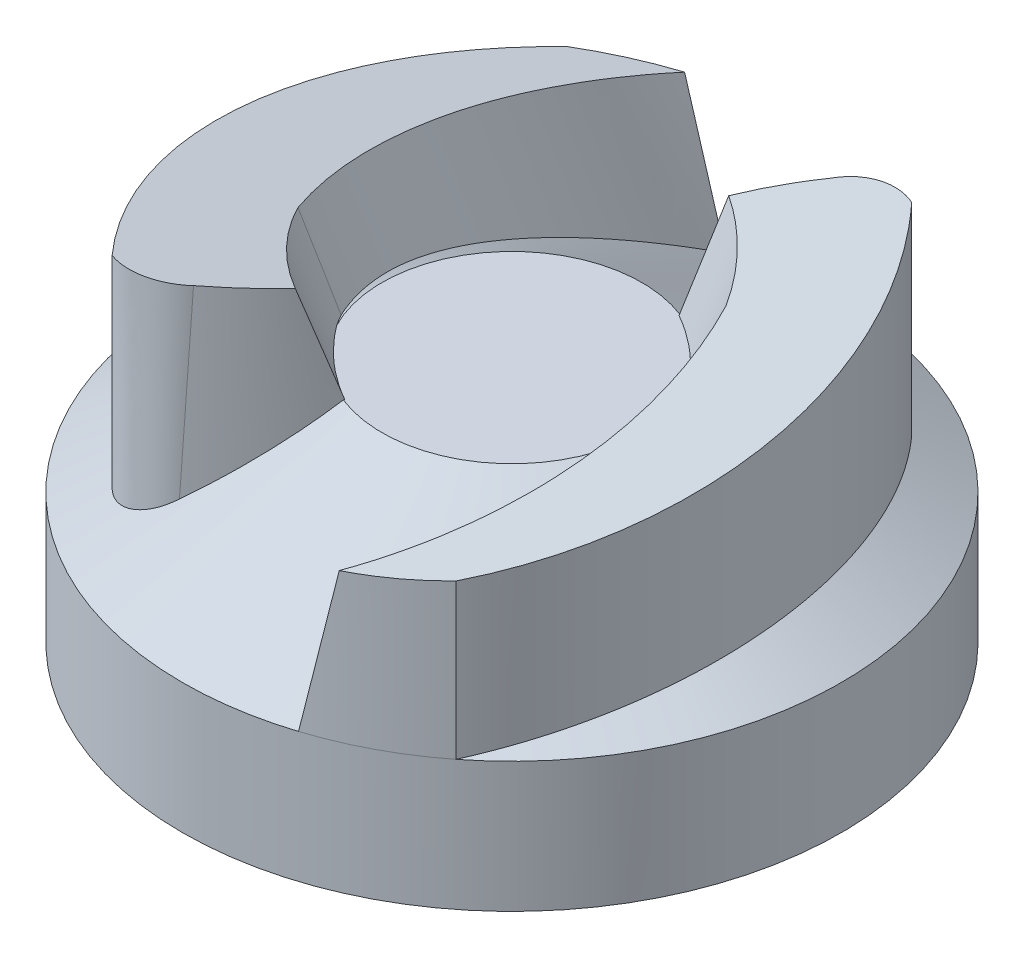
SolidWorks part; units mm, degrees
material "Сталь 3 ГОСТ 535-88"
ref_plane "Спереди" through (0, 0, 0) normal (0, 0, 1) x (1, 0, 0)
ref_plane "Сверху" through (0, 0, 0) normal (0, 1, 0) x (1, 0, 0)
ref_plane "Справа" through (0, 0, 0) normal (1, 0, 0) x (0, 0, -1)
ref_plane "Плоскость1" through (0, 80, 0) normal (0, 1, 0) x (1, 0, 0)
ref_plane "Плоскость2" through (0, 29, 0) normal (0, 1, 0) x (1, 0, 0)
sketch "Эскиз1" plane through (0, 0, 0) normal (0, 0, 1) x (1, 0, 0)
  line L0 (0, 0) -> (0, -40.7027) construction
  line L1 (0, 0) -> (-73.5, 0)
  line L2 (-73.5, 0) -> (-73.5, 29)
  line L3 (-73.5, 29) -> (-29, 55)
  line L4 (-29, 55) -> (0, 55)
  line L5 (0, 55) -> (0, 0)
  dimension "D1" = 147
  dimension "D2" = 58
  dimension "D3" = 29
  dimension "D4" = 55
revolve "Повернуть1" add sketch "Эскиз1" angle 360 about L0
sketch "Эскиз2" plane through (0, 29, 0) normal (0, -1, 0) x (-1, 0, 0)
  line L0 (0, 0) -> (0, -103.2253) construction
  line L1 (0, 0) -> (73.5, 0) construction
  circle A0 centre (0, 0) radius 73.5 construction
  arc A1 (39.4665, -49.6948) -> (45.3803, 57.8177) centre (-23.2537, 7.674) ccw
  arc A3 (5, -19.3649) -> (25, -50) centre (88.7887, 13.4902) ccw
  arc A5 (5, -19.3649) -> (20, -5.5766) centre (-13.6772, 16.0069) ccw
  arc A6 (20, -5.5766) -> (22.4109, 70) centre (-54.8846, 34.639) ccw
  arc A7 (39.4665, -49.6948) -> (25, -50) centre (32.0876, -42.9455) cw
  arc A8 (45.3803, 57.8177) -> (22.4109, 70) centre (0, 0) ccw
  circle A9 centre (0, 0) radius 20 construction
  point P5 (9.9598, -22.9304)
  point P8 (27, -8.0753)
  point P9 (27, -3.5453)
  point P12 (28, -7.5498)
  point P16 (0, 0)
  point P17 (27, 1.6225)
  point P20 (22.4109, 70)
  point P22 (27, -5.5766)
  dimension "D1" = 10
  dimension "D2" = 10
  dimension "D4" = 90
  dimension "D5" = 85
  dimension "D6" = 26
  dimension "D9" = 85
  dimension "D11" = 40
  dimension "D12" = 40
  dimension "D3" = 50
  dimension "D7" = 20
  dimension "D8" = 70
  dimension "D10" = 50
sketch "Эскиз3" plane through (0, 80, 0) normal (0, 1, 0) x (1, 0, 0)
  arc A0 (-22.4109, 70) -> (-45.3803, 57.8177) centre (0, 0) ccw construction
  arc A1 (-22.4109, 70) -> (-20, -5.5766) centre (54.8846, 34.639) ccw construction
  arc A2 (-20, -5.5766) -> (-5, -19.3649) centre (13.6772, 16.0069) ccw construction
  arc A3 (-25, -50) -> (-5, -19.3649) centre (-88.7887, 13.4902) ccw construction
  arc A4 (-39.4665, -49.6948) -> (-25, -50) centre (-32.0876, -42.9455) ccw construction
  arc A5 (-45.3803, 57.8177) -> (-39.4665, -49.6948) centre (23.2537, 7.674) ccw construction
  arc A6 (-32.4109, 65.968) -> (-45.3803, 57.8177) centre (0, 0) ccw
  arc A7 (-22.4109, 70) -> (-20, -5.5766) centre (54.8846, 34.639) ccw construction
  arc A8 (-20, -5.5766) -> (-5, -19.3649) centre (13.6772, 16.0069) ccw construction
  arc A9 (-25, -50) -> (-13.2139, -35.3815) centre (-88.7887, 13.4902) ccw construction
  arc A10 (-39.4665, -49.6948) -> (-25, -50) centre (-32.0876, -42.9455) ccw construction
  arc A11 (-45.3803, 57.8177) -> (-39.4665, -49.6948) centre (23.2537, 7.674) ccw
  arc A12 (-32.4109, 65.968) -> (-35, -15.4059) centre (40.8751, 22.9081) ccw
  arc A13 (-35, -15.4059) -> (-15.8023, -33.8649) centre (13.6772, 16.0069) ccw
  arc A14 (-39.4665, -49.6948) -> (-25.1312, -45.816) centre (-34.8047, -38.4945) ccw
  arc A15 (-25.1312, -45.816) -> (-15.8023, -33.8649) centre (-88.7828, 13.4868) ccw
  point P14 (-8.7557, -34.0749)
  point P16 (-29.4799, 67.3289)
  point P17 (-33.1267, 60.0576)
  point P18 (-33.1267, 60.0576)
  point P19 (-16.6321, -28.6706)
  point P20 (-16.2664, -28.6706)
  point P21 (0, 0)
  point P22 (0, 0)
  point P24 (0, 0)
  point P25 (-16.2664, -28.6706)
  point P26 (-33.4161, -13.3927)
  point P27 (-29.5529, -18.868)
  point P28 (0, 0)
  point P29 (-12.6165, -29.9501)
  point P30 (-12.6165, -29.9501)
  point P31 (-21.4293, -24.7743)
  point P32 (-13.2924, -31.42)
  point P33 (0, 0)
  point P34 (0, 0)
  point P35 (0, 0)
  point P36 (-12.6165, -29.9501)
  point P37 (-12.6165, -29.9501)
  point P38 (-12.6165, -29.9501)
  point P39 (-12.6165, -29.9501)
  point P40 (0, 0)
  point P41 (-12.6165, -29.9501)
  point P42 (-19.6491, -29.0545)
  point P43 (-27, -27.1944)
  point P49 (-39.2736, -49.8999)
  dimension "D1" = 18
  dimension "D2" = 85
  dimension "D3" = 85
  dimension "D4" = 35
  dimension "D7" = 0.0068
  dimension "D8" = 12.1318
  dimension "D5" = 10
  dimension "D6" = 3
  dimension "D9" = 14.5
loft "По сечениям2" add profiles "Эскиз2", "Эскиз3"
sketch "Эскиз6" plane through (0, 0, 0) normal (1, 0, 0) x (0, 0, -1)
  line L0 (67.3911, 62) -> (-50.6262, 80)
  line L1 (-50.6262, 80) -> (-50.6262, 96.1943)
  line L2 (-50.6262, 96.1943) -> (67.3911, 98.7119)
  line L3 (67.3911, 98.7119) -> (67.3911, 62)
  line L4 (70, 29) -> (65.968, 80) construction
  point P4 (-52.9454, 80)
  point P5 (67.3911, 62.0003)
  point P10 (63.3845, 98.4926)
  dimension "D1" = 62
extrude "Вырез-Вытянуть1" cut sketch "Эскиз6" against normal through all both and the other way through all
pattern_circular "Круговой массив1" count 2 over 360 about axis through (0, 0, 0) along (0, 1, 0) of "По сечениям2"
sketch "Эскиз7" plane through (0, 0, 0) normal (1, 0, 0) x (0, 0, -1)
  line L0 (50.6262, 80) -> (50.6262, 117.4168)
  line L1 (50.6262, 117.4168) -> (-67.3911, 118.7919)
  line L2 (-67.3911, 118.7919) -> (-67.3911, 62)
  line L3 (-67.3911, 62) -> (50.6262, 80)
  line L4 (-70, 29) -> (-65.968, 80) construction
  point P2 (-68.4844, 48.1712)
  point P8 (50.6262, 80)
  dimension "D1" = 62
extrude "Вырез-Вытянуть2" cut sketch "Эскиз7" along normal through all
